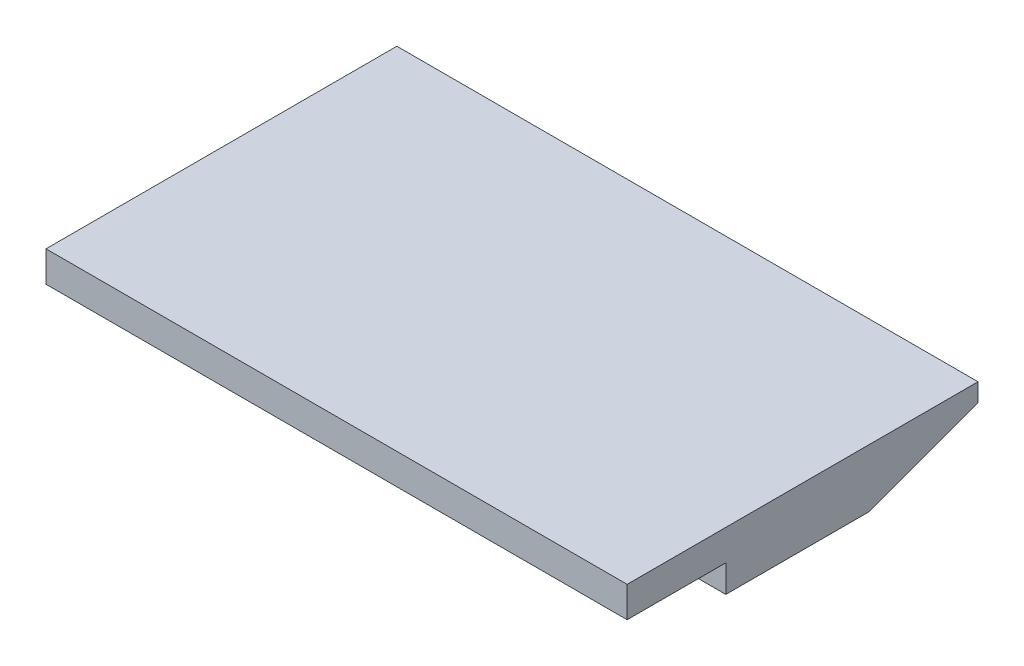
SolidWorks part; units mm, degrees
ref_plane "Ebene vorne" through (0, 0, 0) normal (0, 0, 1) x (1, 0, 0)
ref_plane "Ebene oben" through (0, 0, 0) normal (0, 1, 0) x (1, 0, 0)
ref_plane "Ebene rechts" through (0, 0, 0) normal (1, 0, 0) x (0, 0, -1)
sketch "Skizze1" plane through (0, 0, 0) normal (0, 1, 0) x (1, 0, 0)
  line L1 (-265, -160) -> (265, -160)
  line L2 (-265, -160) -> (-265, 160)
  line L3 (-265, 160) -> (265, 160)
  line L4 (265, -160) -> (265, 160)
  line L5 (-265, -160) -> (265, 160) construction
  line L6 (-265, 160) -> (265, -160) construction
  point P0 (0, 0)
  dimension "D1" = 530
  dimension "D2" = 320
extrude "Aufsatz-Linear austragen1" add sketch "Skizze1" along normal blind 53
chamfer "Fase1" distance 100 angle 20 1 edges at (0, 0, -160)
sketch "Skizze2" plane through (265, 0, 0) normal (1, 0, 0) x (0, 0, -1)
  line L0 (-70, 0) -> (-70, 25)
  line L1 (-160, 0) -> (60, 0) construction
  line L2 (-70, 25) -> (-160, 25)
  line L3 (-160, 25) -> (-160, 0)
  line L4 (-160, 0) -> (-70, 0)
  dimension "D1" = 25
  dimension "D2" = 90
extrude "Schnitt-Linear austragen1" cut sketch "Skizze2" against normal up to vertex (530 mm away)
